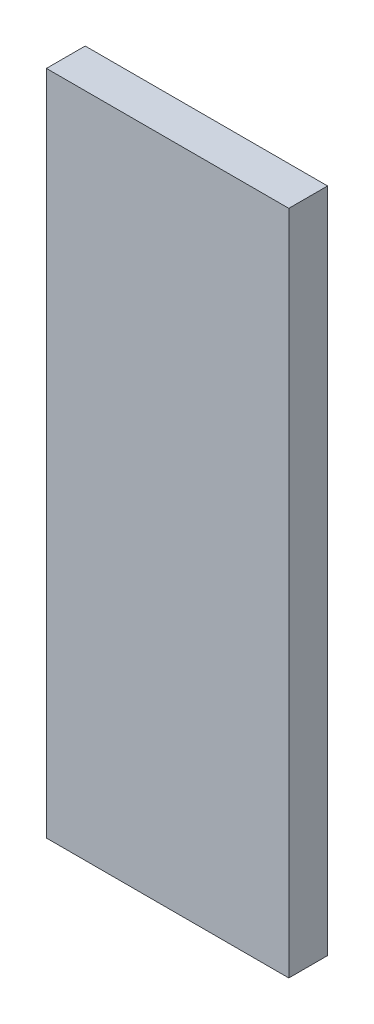
SolidWorks part; units mm, degrees
material "1.0553 (S355J0)"
ref_plane "Front Plane" through (0, 0, 0) normal (0, 0, 1) x (1, 0, 0)
ref_plane "Top Plane" through (0, 0, 0) normal (0, 1, 0) x (1, 0, 0)
ref_plane "Right Plane" through (0, 0, 0) normal (1, 0, 0) x (0, 0, -1)
sketch "Sketch1" plane through (0, 0, 0) normal (0, 0, 1) x (1, 0, 0)
  line L0 (0, -260.9223) -> (0, 214.8058) construction
  line L1 (-250, 0) -> (250, 0)
  line L2 (-250, 0) -> (-250, 1375)
  line L3 (-250, 1375) -> (250, 1375)
  line L4 (250, 0) -> (250, 1375)
  dimension "D1" = 500
  dimension "D2" = 1375
extrude "Boss-Extrude1" add sketch "Sketch1" against normal blind 80
